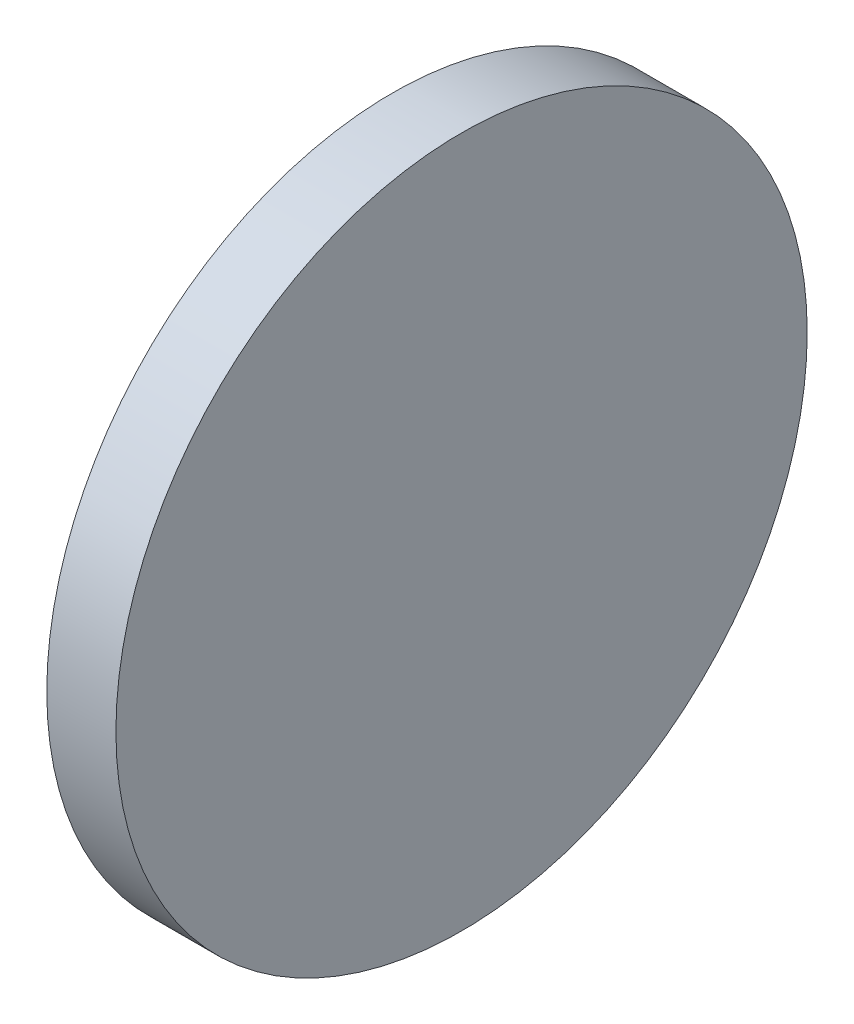
SolidWorks part; units mm, degrees
ref_plane "前视基准面" through (0, 0, 0) normal (0, 0, 1) x (1, 0, 0)
ref_plane "上视基准面" through (0, 0, 0) normal (0, 1, 0) x (1, 0, 0)
ref_plane "右视基准面" through (0, 0, 0) normal (1, 0, 0) x (0, 0, -1)
sketch "草图1" plane through (0, 0, 0) normal (1, 0, 0) x (0, 0, -1)
  circle A0 centre (0, 0) radius 7.5
extrude "凸台-拉伸1" add sketch "草图1" along normal blind 1.5
